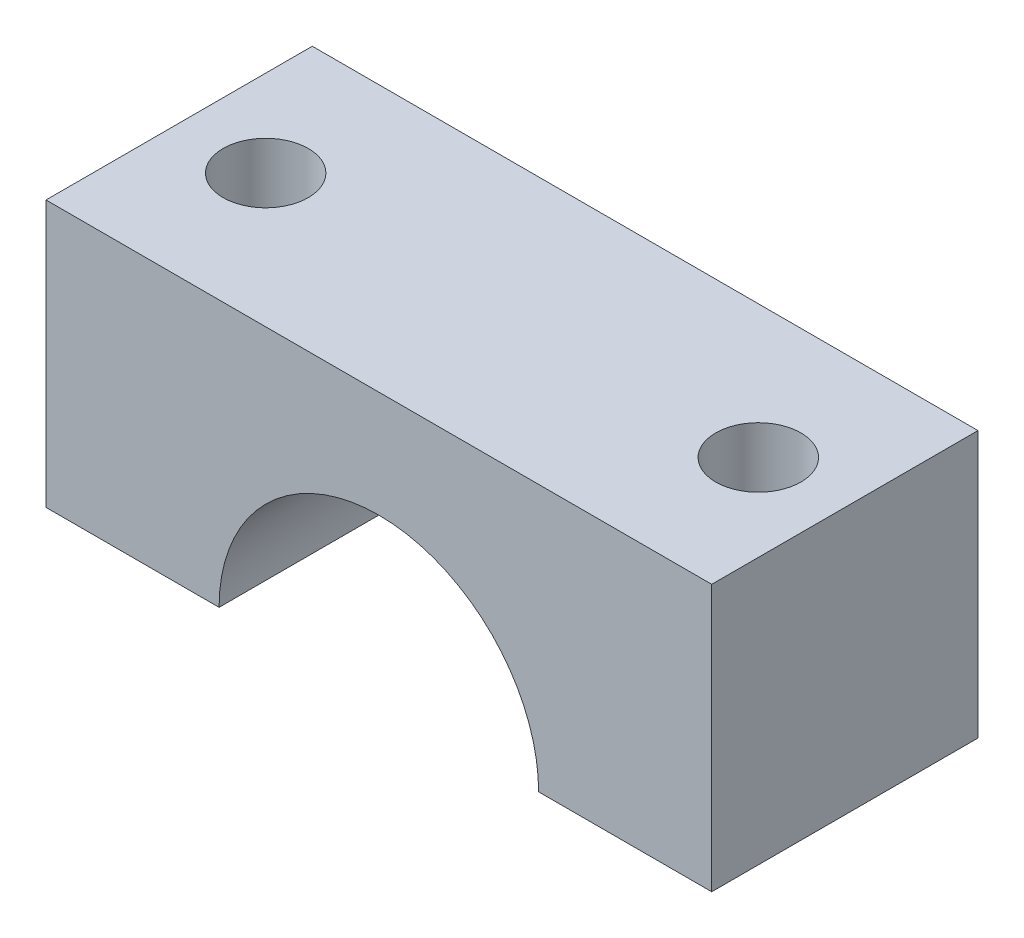
SolidWorks part; units mm, degrees
ref_plane "Front Plane" through (0, 0, 0) normal (0, 0, 1) x (1, 0, 0)
ref_plane "Top Plane" through (0, 0, 0) normal (0, 1, 0) x (1, 0, 0)
ref_plane "Right Plane" through (0, 0, 0) normal (1, 0, 0) x (0, 0, -1)
sketch "Sketch1" plane through (0, 0, 0) normal (0, 1, 0) x (1, 0, 0)
  line L1 (-12.5, -5) -> (12.5, -5)
  line L2 (-12.5, -5) -> (-12.5, 5)
  line L3 (-12.5, 5) -> (12.5, 5)
  line L4 (12.5, -5) -> (12.5, 5)
  line L5 (-12.5, -5) -> (12.5, 5) construction
  line L6 (-12.5, 5) -> (12.5, -5) construction
  point P0 (0, 0)
  dimension "D1" = 25
  dimension "D2" = 10
extrude "Boss-Extrude1" add sketch "Sketch1" along normal blind 10
sketch "Sketch2" plane through (0, 10, 0) normal (0, 1, 0) x (1, 0, 0)
  line L0 (-12.5, 5) -> (-12.5, -5) construction
  line L1 (12.5, -5) -> (12.5, 5) construction
  circle A0 centre (-9.25, 0) radius 1.6
  circle A1 centre (9.25, 0) radius 1.6
  dimension "D1" = 3.25
  dimension "D2" = 3.25
  dimension "D3" = 3.2
  dimension "D4" = 3.2
extrude "Cut-Extrude1" cut sketch "Sketch2" against normal through all
sketch "Sketch3" plane through (0, 0, 5) normal (0, 0, 1) x (1, 0, 0)
  line L3 (-12.5, 0) -> (12.5, 0) construction
  circle A1 centre (0, 0) radius 6
extrude "Cut-Extrude2" cut sketch "Sketch3" against normal blind 25
